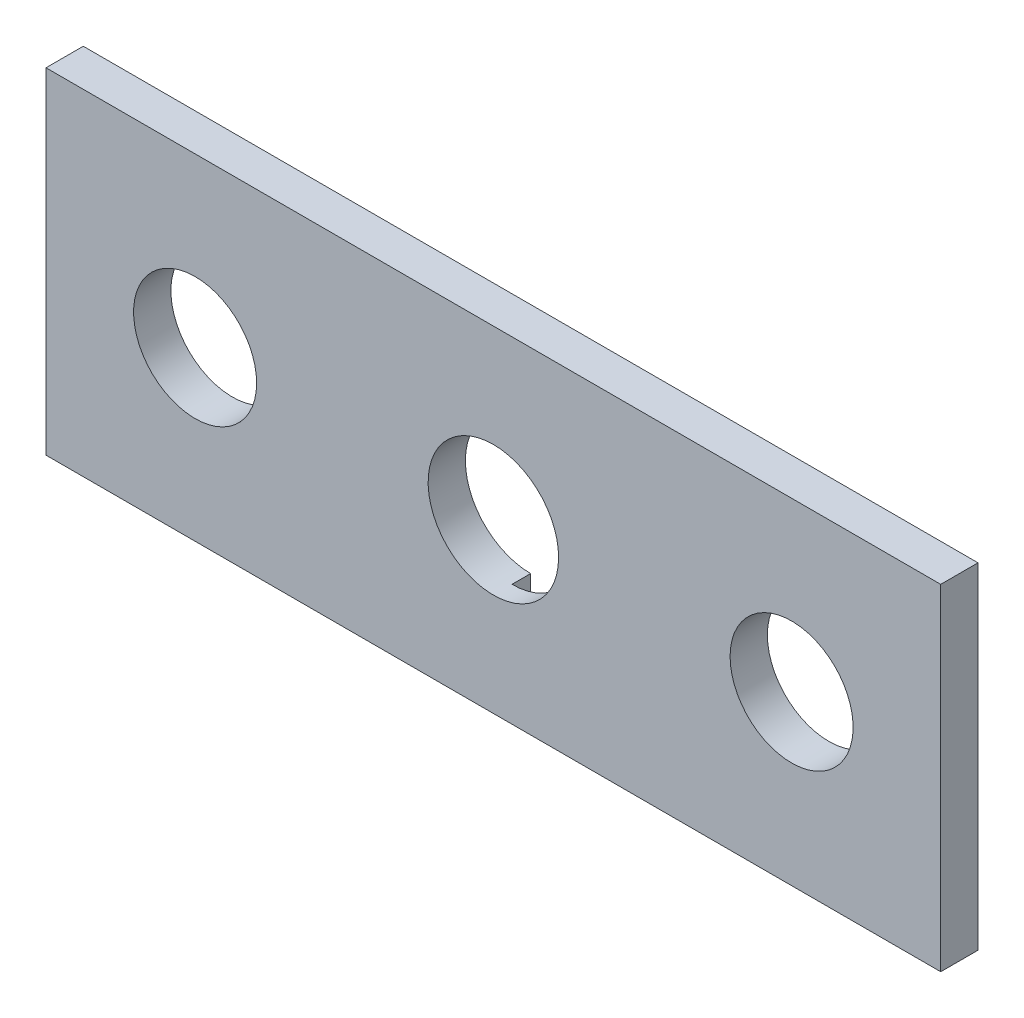
SolidWorks part; units mm, degrees
ref_plane "Alzado" through (0, 0, 0) normal (0, 0, 1) x (1, 0, 0)
ref_plane "Planta" through (0, 0, 0) normal (0, 1, 0) x (1, 0, 0)
ref_plane "Vista lateral" through (0, 0, 0) normal (1, 0, 0) x (0, 0, -1)
sketch "Croquis1" plane through (0, 0, 0) normal (0, 0, 1) x (1, 0, 0)
  line L0 (0, 0) -> (240, 0)
  line L1 (240, 0) -> (240, 90)
  line L2 (240, 90) -> (0, 90)
  line L3 (0, 90) -> (0, 0)
  line L7 (0, 45) -> (40, 45) construction
  circle A0 centre (120, 45) radius 17.5
  circle A3 centre (40, 45) radius 16.5
  circle A4 centre (200, 45) radius 16.5
extrude "Saliente-Extruir1" add sketch "Croquis1" along normal blind 10
sketch "Croquis2" plane through (0, 0, 0) normal (0, 0, -1) x (-1, 0, 0)
  line L0 (-120, 62.5) -> (-120, 67.5)
  line L1 (-120, 67.5) -> (-165, 67.5)
  line L2 (-165, 67.5) -> (-165, 22.5)
  line L3 (-165, 22.5) -> (-120, 22.5)
  line L4 (-120, 22.5) -> (-120, 27.5)
  circle A0 centre (-120, 45) radius 17.5 construction
  arc A1 (-120, 62.5) -> (-120, 27.5) centre (-120, 45) ccw
extrude "Cortar-Extruir1" cut sketch "Croquis2" against normal blind 5
